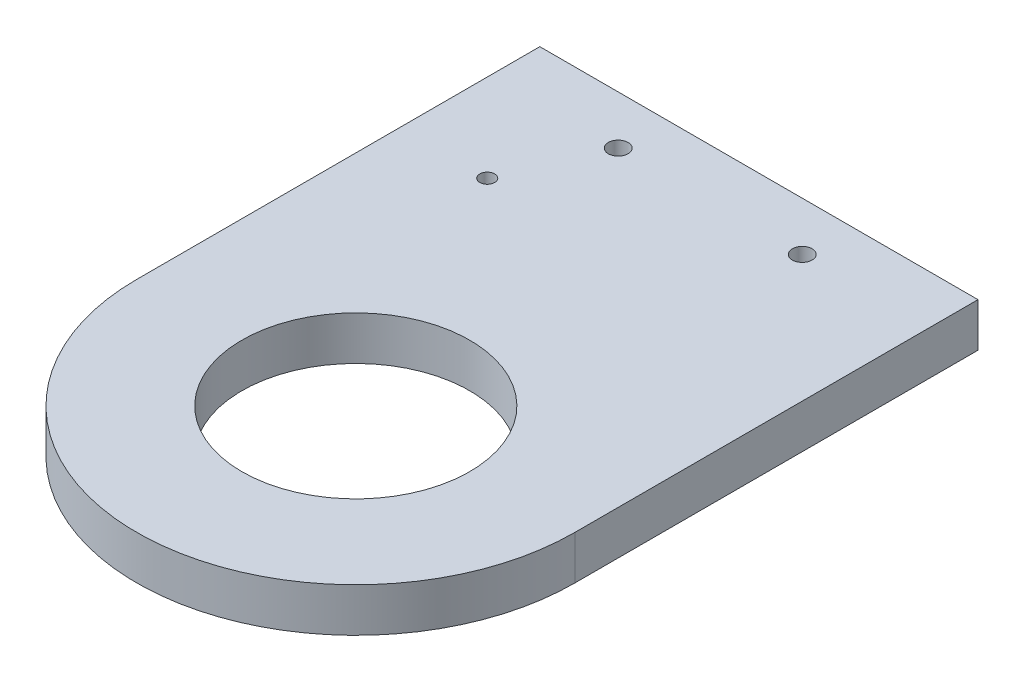
SolidWorks part; units mm, degrees
material "Aleación 6061"
ref_plane "Alzado" through (0, 0, 0) normal (0, 0, 1) x (1, 0, 0)
ref_plane "Planta" through (0, 0, 0) normal (0, 1, 0) x (1, 0, 0)
ref_plane "Vista lateral" through (0, 0, 0) normal (1, 0, 0) x (0, 0, -1)
sketch "Sk_Pared" plane through (0, 0, 0) normal (0, 1, 0) x (1, 0, 0)
  line L1 (-50, -170) -> (50, -170)
  line L2 (-50, -170) -> (-50, -78)
  line L3 (-50, -78) -> (50, -78)
  line L4 (50, -170) -> (50, -78)
  line L5 (-50, -170) -> (50, -78) construction
  line L6 (-50, -78) -> (50, -170) construction
  point P0 (0, -124)
  dimension "D1" = 100
  dimension "D2" = 92
  dimension "D3" = 124
extrude "Pared" add sketch "Sk_Pared" along normal blind 10 from offset 29.75
sketch "Sk_Cabeza" plane through (0, 0, 0) normal (0, 1, 0) x (1, 0, 0)
  circle A0 centre (0, -170) radius 50
  dimension "D1" = 100
  dimension "D2" = 170
extrude "Cabeza" add sketch "Sk_Cabeza" along normal blind 10 from offset 29.75
sketch "Sk_Paso_cubo_J2" plane through (0, 0, 0) normal (0, 1, 0) x (1, 0, 0)
  circle A0 centre (0, -170) radius 26
  dimension "D1" = 52
  dimension "D2" = 170
extrude "Paso_cubo_J2" cut sketch "Sk_Paso_cubo_J2" along normal blind 10 from offset 29.75
sketch "Sk_Pasantes_M4_angulos" plane through (0, 0, 0) normal (0, 1, 0) x (1, 0, 0)
  circle A0 centre (-21, -89.11) radius 2.25
  circle A1 centre (21, -89.11) radius 2.25
  dimension "D1" = 4.5
  dimension "D4" = 4.5
  dimension "D2" = 21
  dimension "D3" = 89.11
  dimension "D5" = 21
  dimension "D6" = 89.11
extrude "Pasantes_M4_angulos" cut sketch "Sk_Pasantes_M4_angulos" along normal blind 10 from offset 29.75
sketch "Sk_Pasante_M3_cincho" plane through (0, 0, 0) normal (0, 1, 0) x (1, 0, 0)
  circle A0 centre (-30, -110) radius 1.7
  dimension "D1" = 3.4
  dimension "D2" = 30
  dimension "D3" = 110
extrude "Pasante_M3_cincho" cut sketch "Sk_Pasante_M3_cincho" along normal blind 10 from offset 29.75
